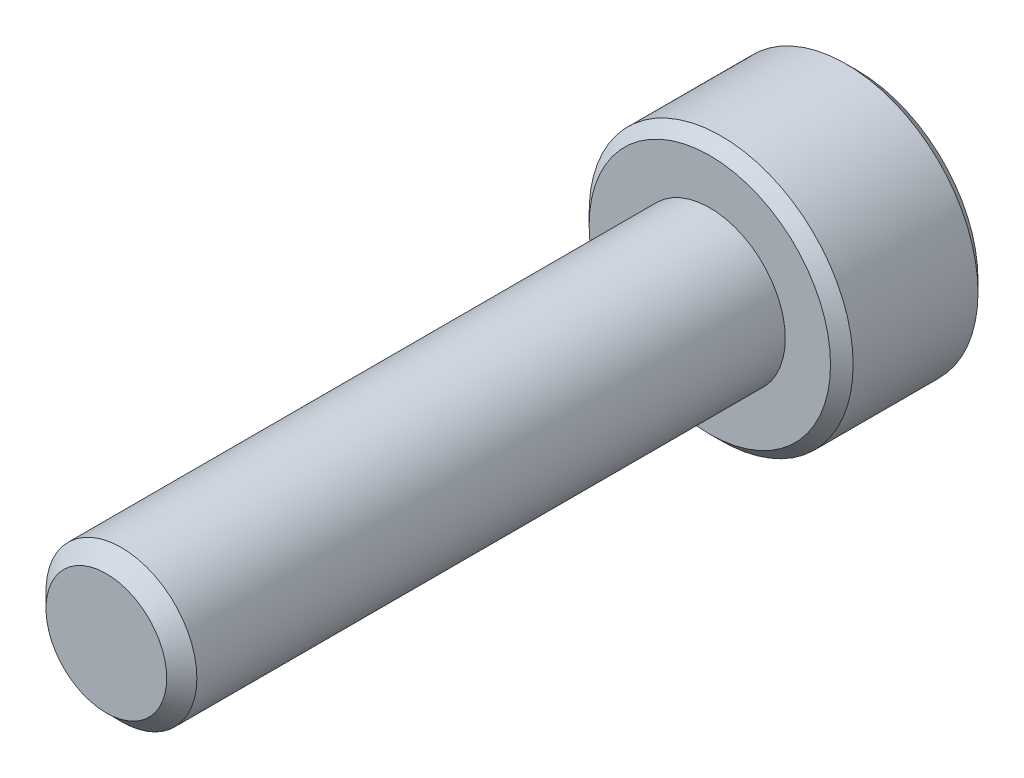
SolidWorks part; units mm, degrees
material "AISI 304"
ref_plane "前视基准面" through (0, 0, 0) normal (0, 0, 1) x (1, 0, 0)
ref_plane "上视基准面" through (0, 0, 0) normal (0, 1, 0) x (1, 0, 0)
ref_plane "右视基准面" through (0, 0, 0) normal (1, 0, 0) x (0, 0, -1)
sketch "草图1" plane through (0, 0, 0) normal (0, 0, 1) x (1, 0, 0)
  circle A0 centre (0, 0) radius 3.5
  dimension "D1" = 7
extrude "凸台-拉伸1" add sketch "草图1" along normal blind 3.91
sketch "草图2" plane through (0, 0, 3.91) normal (0, 0, 1) x (1, 0, 0)
  circle A0 centre (0, 0) radius 2
  dimension "D1" = 4
extrude "凸台-拉伸2" add sketch "草图2" along normal blind 16
sketch "草图3" plane through (0, 0, 0) normal (0, 0, -1) x (-1, 0, 0)
  line L1 (0, 1.7609) -> (-1.525, 0.8805)
  line L2 (-1.525, 0.8805) -> (-1.525, -0.8805)
  line L3 (-1.525, -0.8805) -> (0, -1.7609)
  line L4 (0, -1.7609) -> (1.525, -0.8805)
  line L5 (1.525, -0.8805) -> (1.525, 0.8805)
  line L6 (1.525, 0.8805) -> (0, 1.7609)
  circle A0 centre (0, 0) radius 1.525 construction
  dimension "D1" = 3.05
extrude "切除-拉伸1" cut sketch "草图3" against normal blind 2
chamfer "倒角1" distance 0.4 angle 45 1 edges at (2, 0, 19.91)
chamfer "倒角2" distance 0.3 angle 45 2 edges at (3.5, 0, 3.91) (3.5, 0, 0)
